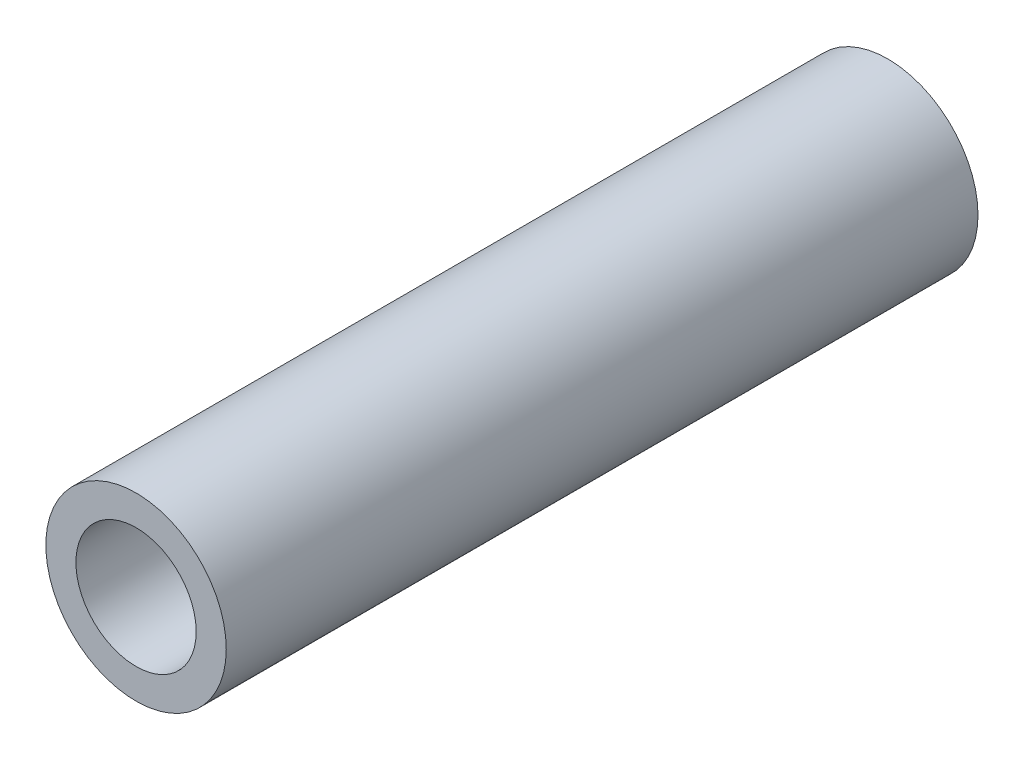
SolidWorks part; units mm, degrees
material "1.4000 (X6Cr13)"
ref_plane "正面" through (0, 0, 0) normal (0, 0, 1) x (1, 0, 0)
ref_plane "平面" through (0, 0, 0) normal (0, 1, 0) x (1, 0, 0)
ref_plane "右側面" through (0, 0, 0) normal (1, 0, 0) x (0, 0, -1)
sketch "ｽｹｯﾁ1" plane through (0, 0, 0) normal (0, 0, 1) x (1, 0, 0)
  circle A0 centre (0, 0) radius 3
  circle A1 centre (0, 0) radius 2
  dimension "D1" = 6
  dimension "D2" = 4
extrude "ﾎﾞｽ - 押し出し1" add sketch "ｽｹｯﾁ1" along normal blind 25
